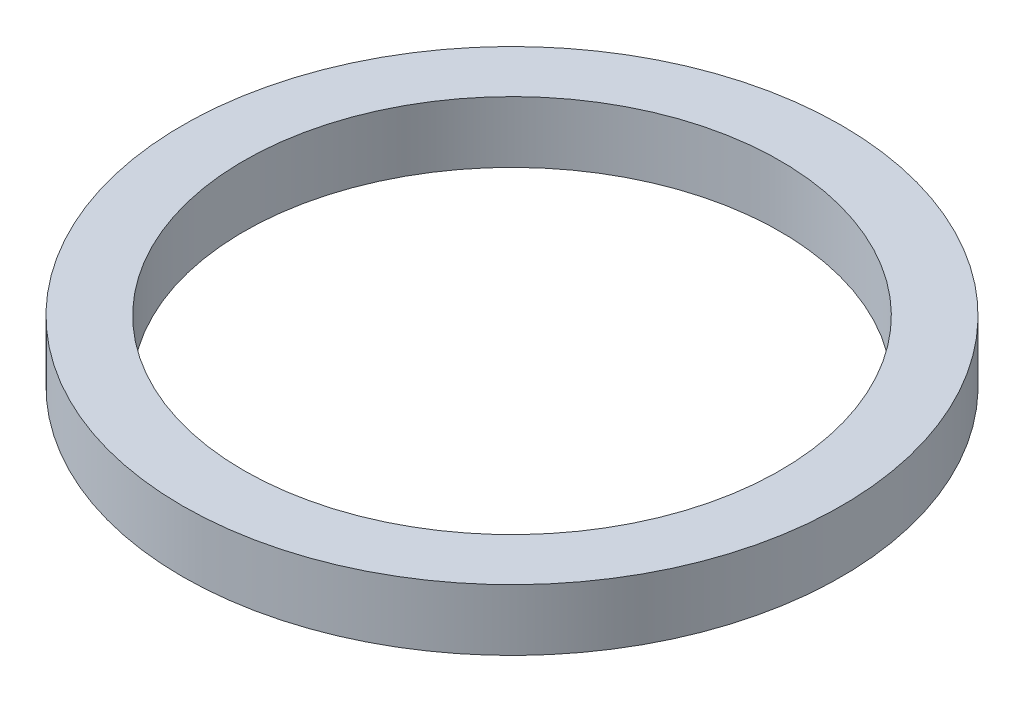
SolidWorks part; units mm, degrees
ref_plane "前视基准面" through (0, 0, 0) normal (0, 0, 1) x (1, 0, 0)
ref_plane "上视基准面" through (0, 0, 0) normal (0, 1, 0) x (1, 0, 0)
ref_plane "右视基准面" through (0, 0, 0) normal (1, 0, 0) x (0, 0, -1)
other "Configuration Table"
sketch "草图1" plane through (0, 0, 0) normal (0, 1, 0) x (1, 0, 0)
  circle A0 centre (0, 0) radius 35
  circle A1 centre (0, 0) radius 43
  dimension "D1" = 70
  dimension "D2" = 86
extrude "凸台-拉伸1" add sketch "草图1" along normal blind 8
